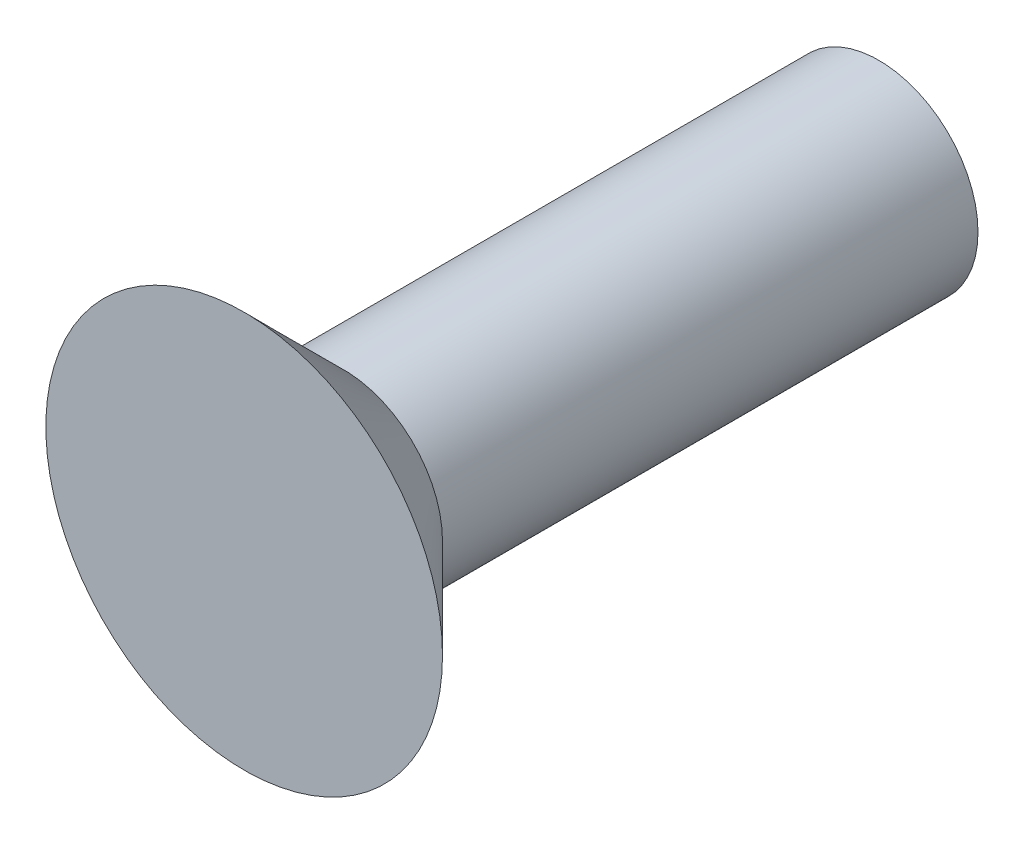
SolidWorks part; units mm, degrees
ref_plane "Front Plane" through (0, 0, 0) normal (0, 0, 1) x (1, 0, 0)
ref_plane "Top Plane" through (0, 0, 0) normal (0, 1, 0) x (1, 0, 0)
ref_plane "Right Plane" through (0, 0, 0) normal (1, 0, 0) x (0, 0, -1)
sketch "Sketch1" plane through (0, 0, 0) normal (0, 0, 1) x (1, 0, 0)
  circle A0 centre (0, 0) radius 2.5
extrude "Head_D5_90deg" add sketch "Sketch1" against normal blind 1.25 draft 45
sketch "Sketch2" plane through (0, 0, 0) normal (0, 0, 1) x (1, 0, 0)
  circle A0 centre (0, 0) radius 1.25
extrude "M2p5x0p45_Thread_Envelope" add sketch "Sketch2" along normal blind 6.75 from offset 8
